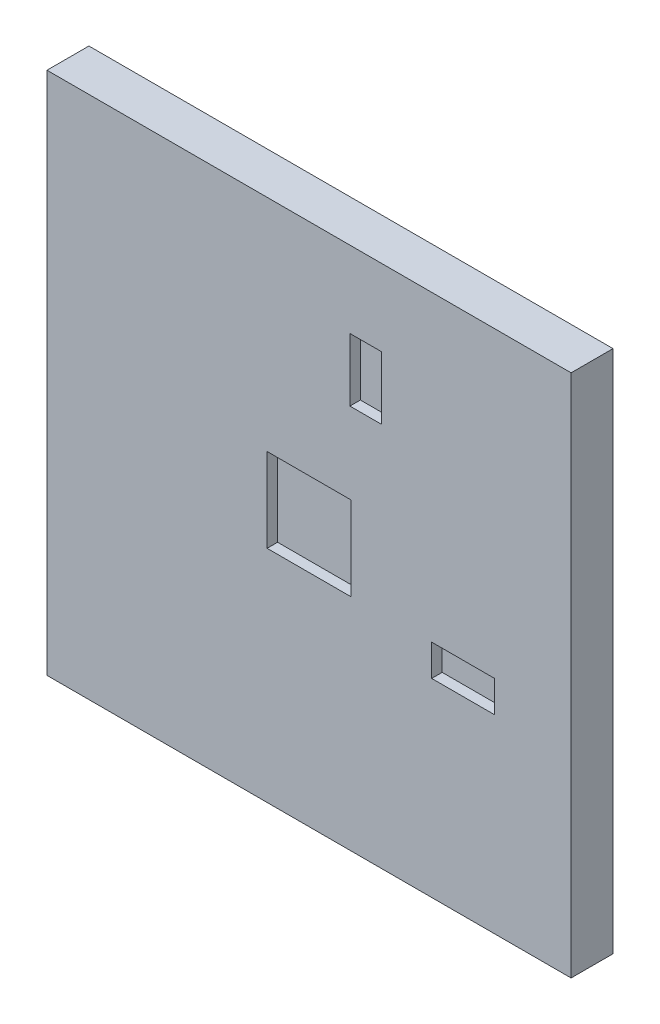
SolidWorks part; units mm, degrees
ref_plane "Ön Düzlem" through (0, 0, 0) normal (0, 0, 1) x (1, 0, 0)
ref_plane "Üst Düzlem" through (0, 0, 0) normal (0, 1, 0) x (1, 0, 0)
ref_plane "Sağ Düzlem" through (0, 0, 0) normal (1, 0, 0) x (0, 0, -1)
sketch "Sketch1" plane through (0, 0, 0) normal (0, 0, 1) x (1, 0, 0)
  line L1 (147.0484, -195.9037) -> (-102.9516, -195.9037)
  line L2 (147.0484, -195.9037) -> (147.0484, 54.0963)
  line L3 (147.0484, 54.0963) -> (-102.9516, 54.0963)
  line L4 (-102.9516, -195.9037) -> (-102.9516, 54.0963)
  dimension "D1" = 250
  dimension "D2" = 250
extrude "Boss-Extrude1" add sketch "Sketch1" along normal blind 20
sketch "Sketch2" plane through (0, 0, 20) normal (0, 0, 1) x (1, 0, 0)
  line L0 (147.0484, -195.9037) -> (147.0484, 54.0963) construction
  line L1 (41.5484, 17.5963) -> (56.5484, 17.5963)
  line L2 (41.5484, 17.5963) -> (41.5484, -12.4037)
  line L3 (41.5484, -12.4037) -> (56.5484, -12.4037)
  line L4 (56.5484, 17.5963) -> (56.5484, -12.4037)
  line L5 (80.5484, -105.4037) -> (110.5484, -105.4037)
  line L6 (80.5484, -105.4037) -> (80.5484, -90.4037)
  line L7 (80.5484, -90.4037) -> (110.5484, -90.4037)
  line L8 (110.5484, -105.4037) -> (110.5484, -90.4037)
  line L9 (2.0484, -50.9037) -> (42.0484, -50.9037)
  line L10 (2.0484, -50.9037) -> (2.0484, -90.9037)
  line L11 (2.0484, -90.9037) -> (42.0484, -90.9037)
  line L12 (42.0484, -50.9037) -> (42.0484, -90.9037)
  line L13 (-102.9516, -195.9037) -> (147.0484, -195.9037) construction
  line L14 (-102.9516, 54.0963) -> (-102.9516, -195.9037) construction
  line L15 (147.0484, 54.0963) -> (-102.9516, 54.0963) construction
  dimension "D1" = 15
  dimension "D2" = 30
  dimension "D3" = 30
  dimension "D4" = 15
  dimension "D5" = 40
  dimension "D6" = 40
  dimension "D7" = 90.5
  dimension "D8" = 36.5
  dimension "D9" = 90.5
  dimension "D10" = 105
  dimension "D11" = 105
  dimension "D12" = 36.5
extrude "Cut-Extrude1" cut sketch "Sketch2" against normal blind 5
